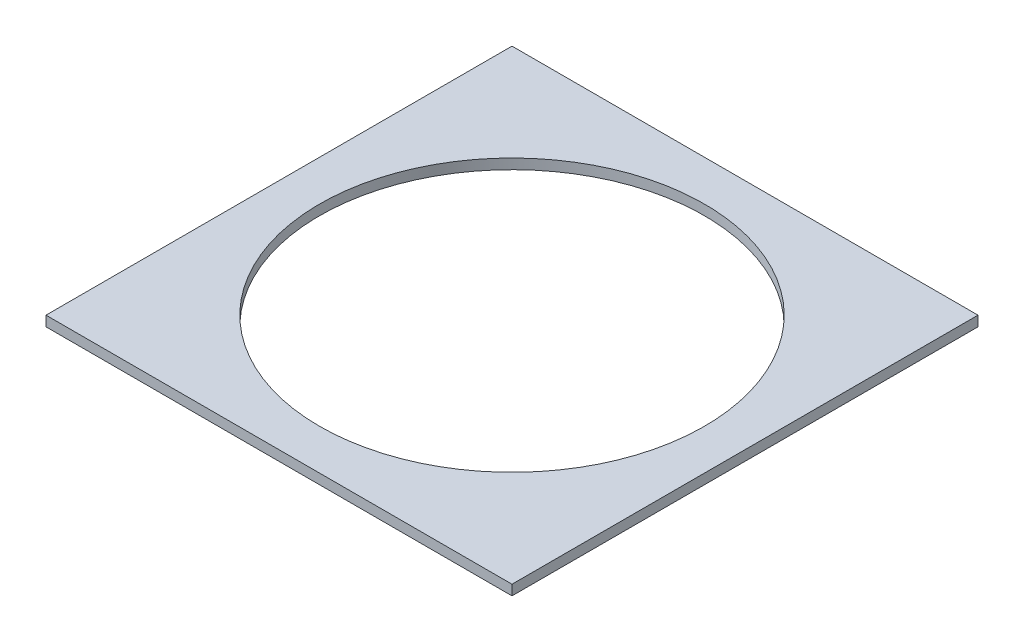
SolidWorks part; units mm, degrees
ref_plane "Front Plane" through (0, 0, 0) normal (0, 0, 1) x (1, 0, 0)
ref_plane "Top Plane" through (0, 0, 0) normal (0, 1, 0) x (1, 0, 0)
ref_plane "Right Plane" through (0, 0, 0) normal (1, 0, 0) x (0, 0, -1)
sketch "Sketch1" plane through (0, 0, 0) normal (0, 1, 0) x (1, 0, 0)
  line L1 (-146.05, 146.05) -> (146.05, 146.05)
  line L2 (-146.05, 146.05) -> (-146.05, -146.05)
  line L3 (-146.05, -146.05) -> (146.05, -146.05)
  line L4 (146.05, 146.05) -> (146.05, -146.05)
  dimension "D1" = 292.1
  dimension "D2" = 292.1
  dimension "D3" = 146.05
  dimension "D4" = 146.05
extrude "Boss-Extrude1" add sketch "Sketch1" along normal blind 6.35
sketch "Sketch2" plane through (0, 6.35, 0) normal (0, 1, 0) x (1, 0, 0)
  circle A0 centre (0, 0) radius 120.65
  dimension "D1" = 241.3
extrude "Cut-Extrude1" cut sketch "Sketch2" against normal blind 6.35
